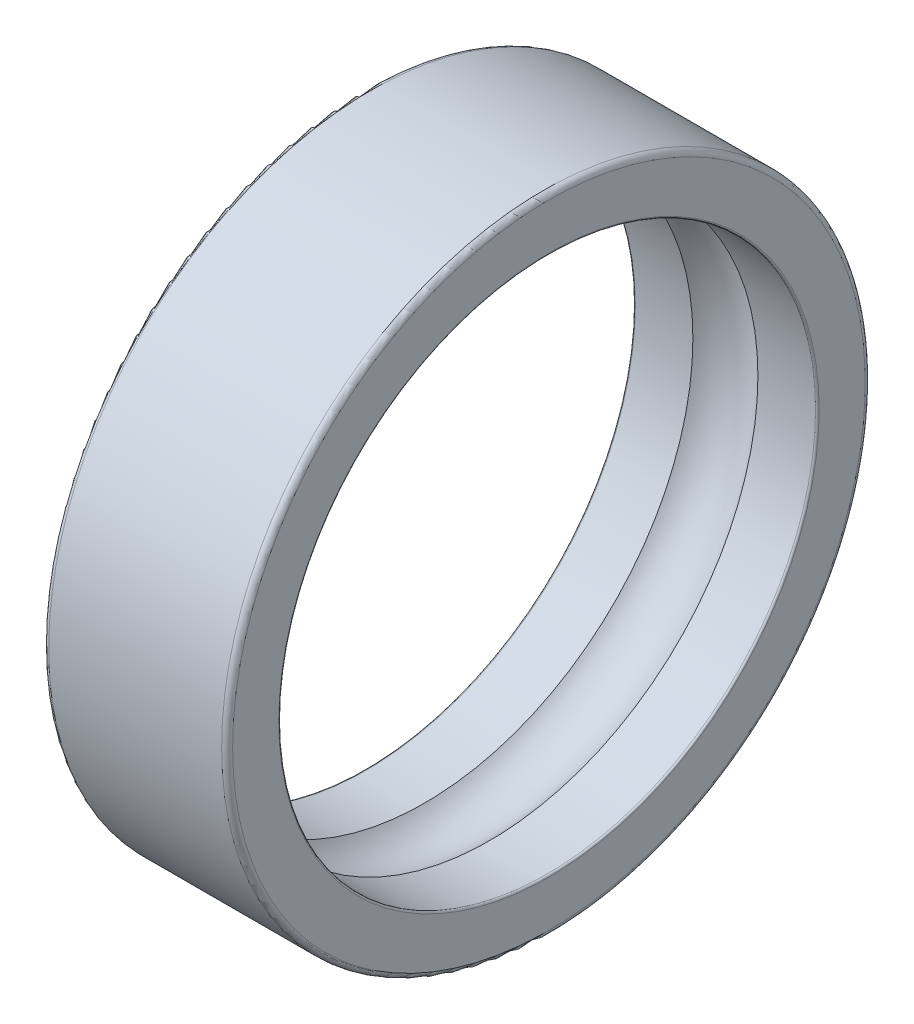
SolidWorks part; units mm, degrees
ref_plane "Plan de face" through (0, 0, 0) normal (0, 0, 1) x (1, 0, 0)
ref_plane "Plan de dessus" through (0, 0, 0) normal (0, 1, 0) x (1, 0, 0)
ref_plane "Plan de droite" through (0, 0, 0) normal (1, 0, 0) x (0, 0, -1)
ref_plane "Plan1" through (0, 0, 0) normal (0, 0, 1) x (1, 0, 0)
sketch "Esquisse1" plane through (0, 0, 0) normal (0, 0, 1) x (1, 0, 0)
  line L0 (0, 17.2) -> (0, 14.695)
  line L1 (0.1, 14.595) -> (3.2322, 14.595)
  line L2 (6.7678, 14.595) -> (9.9, 14.595)
  line L3 (10, 14.695) -> (10, 17.2)
  line L4 (9.7, 17.5) -> (0.3, 17.5)
  line L5 (50, 0) -> (-50, 0) construction
  arc A0 (0, 14.695) -> (0.1, 14.595) centre (0.1, 14.695) ccw
  arc A1 (3.2322, 14.595) -> (6.7678, 14.595) centre (5, 13) cw
  arc A2 (9.9, 14.595) -> (10, 14.695) centre (9.9, 14.695) ccw
  arc A3 (10, 17.2) -> (9.7, 17.5) centre (9.7, 17.2) ccw
  arc A4 (0.3, 17.5) -> (0, 17.2) centre (0.3, 17.2) ccw
revolve "Révolution1" add sketch "Esquisse1" angle 360 about L5
